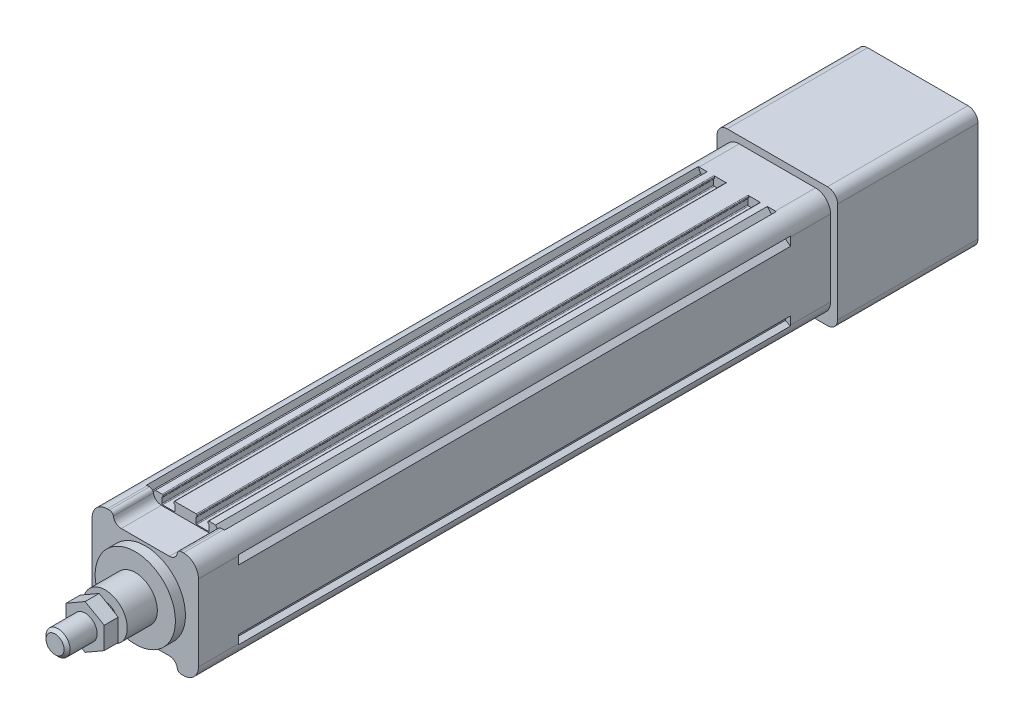
SolidWorks part; units mm, degrees
ref_plane "Front" through (0, 0, 0) normal (0, 0, 1) x (1, 0, 0)
ref_plane "Top" through (0, 0, 0) normal (0, 1, 0) x (1, 0, 0)
ref_plane "Right" through (0, 0, 0) normal (1, 0, 0) x (0, 0, -1)
sketch "草图1" plane through (0, 0, 0) normal (0, 0, 1) x (1, 0, 0)
  line L0 (19.7737, 3) -> (23.3, 3)
  line L1 (23.3, 3) -> (23.3, -3)
  line L2 (23.3, -3) -> (19.7737, -3)
  line L3 (-19.7737, -3) -> (-23.3, -3)
  line L4 (-23.3, -3) -> (-23.3, 3)
  line L5 (-23.3, 3) -> (-19.7737, 3)
  line L6 (-18.2, 24) -> (-19.4434, 26.4869)
  line L7 (-26.4869, 19.4434) -> (-24, 18.2)
  line L8 (-24, 18.2) -> (-24, 17.1)
  line L9 (-24, 17.1) -> (-26.5, 15)
  line L10 (-26.5, 15) -> (-26.5, -15)
  line L11 (-26.5, -15) -> (-24, -17.1)
  line L12 (-24, -17.1) -> (-24, -18.2)
  line L13 (-24, -18.2) -> (-26.4869, -19.4434)
  line L14 (-19.4434, -26.4869) -> (-18.2, -24)
  line L15 (-18.2, -24) -> (-17.1, -24)
  line L16 (-17.1, -24) -> (-15, -26.5)
  line L17 (-15, -26.5) -> (-11.65, -26.5)
  line L18 (-11.25, -26.1) -> (-11.25, -25.6)
  line L19 (-11.65, -25.2) -> (-11.75, -25.2)
  line L20 (-11.75, -25.2) -> (-11.75, -22.4)
  line L21 (-11.35, -22) -> (-5.65, -22)
  line L22 (-5.25, -22.4) -> (-5.25, -25.2)
  line L23 (-5.25, -25.2) -> (-5.35, -25.2)
  line L24 (-5.75, -25.6) -> (-5.75, -26.1)
  line L25 (-5.35, -26.5) -> (5.35, -26.5)
  line L26 (5.75, -26.1) -> (5.75, -25.6)
  line L27 (5.35, -25.2) -> (5.25, -25.2)
  line L28 (5.25, -25.2) -> (5.25, -22.4)
  line L29 (5.65, -22) -> (11.35, -22)
  line L30 (11.75, -22.4) -> (11.75, -25.2)
  line L31 (11.75, -25.2) -> (11.65, -25.2)
  line L32 (11.25, -25.6) -> (11.25, -26.1)
  line L33 (11.65, -26.5) -> (15, -26.5)
  line L34 (15, -26.5) -> (17.1, -24)
  line L35 (17.1, -24) -> (18.2, -24)
  line L36 (18.2, -24) -> (19.4434, -26.4869)
  line L37 (26.4869, -19.4434) -> (24, -18.2)
  line L38 (24, -18.2) -> (24, -17.1)
  line L39 (24, -17.1) -> (26.5, -15)
  line L40 (26.5, -15) -> (26.5, 15)
  line L41 (26.5, 15) -> (24, 17.1)
  line L42 (24, 17.1) -> (24, 18.2)
  line L43 (24, 18.2) -> (26.4869, 19.4434)
  line L44 (19.4434, 26.4869) -> (18.2, 24)
  line L45 (18.2, 24) -> (17.1, 24)
  line L46 (17.1, 24) -> (15, 26.5)
  line L47 (15, 26.5) -> (11.65, 26.5)
  line L48 (11.25, 26.1) -> (11.25, 25.6)
  line L49 (11.65, 25.2) -> (11.75, 25.2)
  line L50 (11.75, 25.2) -> (11.75, 22.4)
  line L51 (11.35, 22) -> (5.65, 22)
  line L52 (5.25, 22.4) -> (5.25, 25.2)
  line L53 (5.25, 25.2) -> (5.35, 25.2)
  line L54 (5.75, 25.6) -> (5.75, 26.1)
  line L55 (5.35, 26.5) -> (-5.35, 26.5)
  line L56 (-5.75, 26.1) -> (-5.75, 25.6)
  line L57 (-5.35, 25.2) -> (-5.25, 25.2)
  line L58 (-5.25, 25.2) -> (-5.25, 22.4)
  line L59 (-5.65, 22) -> (-11.35, 22)
  line L60 (-11.75, 22.4) -> (-11.75, 25.2)
  line L61 (-11.75, 25.2) -> (-11.65, 25.2)
  line L62 (-11.25, 25.6) -> (-11.25, 26.1)
  line L63 (-11.65, 26.5) -> (-15, 26.5)
  line L64 (-15, 26.5) -> (-17.1, 24)
  line L65 (-17.1, 24) -> (-18.2, 24)
  arc A0 (19.7737, 3) -> (-19.7737, 3) centre (0, 0) ccw
  arc A1 (-19.7737, -3) -> (19.7737, -3) centre (0, 0) ccw
  circle A2 centre (19, 19) radius 2.1
  circle A3 centre (19, -19) radius 2.1
  circle A4 centre (-19, -19) radius 2.1
  circle A5 centre (-19, 19) radius 2.1
  arc A6 (-19.4434, 26.4869) -> (-26.4869, 19.4434) centre (-19, 19) ccw
  arc A7 (-26.4869, -19.4434) -> (-19.4434, -26.4869) centre (-19, -19) ccw
  arc A8 (-11.65, -26.5) -> (-11.25, -26.1) centre (-11.65, -26.1) ccw
  arc A9 (-11.25, -25.6) -> (-11.65, -25.2) centre (-11.65, -25.6) ccw
  arc A10 (-11.35, -22) -> (-11.75, -22.4) centre (-11.35, -22.4) ccw
  arc A11 (-5.25, -22.4) -> (-5.65, -22) centre (-5.65, -22.4) ccw
  arc A12 (-5.35, -25.2) -> (-5.75, -25.6) centre (-5.35, -25.6) ccw
  arc A13 (-5.75, -26.1) -> (-5.35, -26.5) centre (-5.35, -26.1) ccw
  arc A14 (5.35, -26.5) -> (5.75, -26.1) centre (5.35, -26.1) ccw
  arc A15 (5.75, -25.6) -> (5.35, -25.2) centre (5.35, -25.6) ccw
  arc A16 (5.65, -22) -> (5.25, -22.4) centre (5.65, -22.4) ccw
  arc A17 (11.75, -22.4) -> (11.35, -22) centre (11.35, -22.4) ccw
  arc A18 (11.65, -25.2) -> (11.25, -25.6) centre (11.65, -25.6) ccw
  arc A19 (11.25, -26.1) -> (11.65, -26.5) centre (11.65, -26.1) ccw
  arc A20 (19.4434, -26.4869) -> (26.4869, -19.4434) centre (19, -19) ccw
  arc A21 (26.4869, 19.4434) -> (19.4434, 26.4869) centre (19, 19) ccw
  arc A22 (11.65, 26.5) -> (11.25, 26.1) centre (11.65, 26.1) ccw
  arc A23 (11.25, 25.6) -> (11.65, 25.2) centre (11.65, 25.6) ccw
  arc A24 (11.35, 22) -> (11.75, 22.4) centre (11.35, 22.4) ccw
  arc A25 (5.25, 22.4) -> (5.65, 22) centre (5.65, 22.4) ccw
  arc A26 (5.35, 25.2) -> (5.75, 25.6) centre (5.35, 25.6) ccw
  arc A27 (5.75, 26.1) -> (5.35, 26.5) centre (5.35, 26.1) ccw
  arc A28 (-5.35, 26.5) -> (-5.75, 26.1) centre (-5.35, 26.1) ccw
  arc A29 (-5.75, 25.6) -> (-5.35, 25.2) centre (-5.35, 25.6) ccw
  arc A30 (-5.65, 22) -> (-5.25, 22.4) centre (-5.65, 22.4) ccw
  arc A31 (-11.75, 22.4) -> (-11.35, 22) centre (-11.35, 22.4) ccw
  arc A32 (-11.65, 25.2) -> (-11.25, 25.6) centre (-11.65, 25.6) ccw
  arc A33 (-11.25, 26.1) -> (-11.65, 26.5) centre (-11.65, 26.1) ccw
extrude "凸台-拉伸1" add sketch "草图1" along normal blind 275
sketch "草图6" plane through (0, 0, 275) normal (0, 0, 1) x (1, 0, 0)
  line L0 (0, 0) -> (19, 0) construction
  line L2 (-26.5, -19) -> (-26.5, 19)
  line L3 (-19, 26.5) -> (-17.9161, 26.5)
  line L4 (26.5, -19) -> (26.5, 19)
  line L5 (-26.5, -26.5) -> (26.5, 26.5) construction
  line L6 (-26.5, 26.5) -> (26.5, -26.5) construction
  line L7 (-12, 21.5) -> (12, 21.5)
  line L9 (19, 26.5) -> (17.9161, 26.5)
  line L10 (19, -26.5) -> (17.9161, -26.5)
  line L11 (-12, -21.5) -> (12, -21.5)
  line L12 (-19, -26.5) -> (-17.9161, -26.5)
  arc A0 (12, 21.5) -> (15.9441, 24.8333) centre (12, 25.5) ccw
  arc A1 (-15.9441, 24.8333) -> (-12, 21.5) centre (-12, 25.5) ccw
  arc A2 (-15.9441, 24.8333) -> (-17.9161, 26.5) centre (-17.9161, 24.5) ccw
  arc A3 (15.9441, 24.8333) -> (17.9161, 26.5) centre (17.9161, 24.5) cw
  arc A4 (-26.5, -19) -> (-19, -26.5) centre (-19, -19) ccw
  arc A5 (19, -26.5) -> (26.5, -19) centre (19, -19) ccw
  arc A6 (26.5, 19) -> (19, 26.5) centre (19, 19) ccw
  arc A7 (-26.5, 19) -> (-19, 26.5) centre (-19, 19) cw
  arc A8 (15.9441, -24.8333) -> (17.9161, -26.5) centre (17.9161, -24.5) ccw
  arc A9 (12, -21.5) -> (15.9441, -24.8333) centre (12, -25.5) cw
  arc A10 (-15.9441, -24.8333) -> (-12, -21.5) centre (-12, -25.5) cw
  arc A11 (-15.9441, -24.8333) -> (-17.9161, -26.5) centre (-17.9161, -24.5) cw
  point P0 (0, 0)
  point P9 (0, 21.5)
  point P13 (20, 20.8461)
  point P16 (-12, 20.8461)
  dimension "D5" = 4
  dimension "D6" = 2
  dimension "D7" = 2
  dimension "D9" = 7.5
  dimension "D1" = 53
  dimension "D2" = 53
  dimension "D3" = 26.5
  dimension "D4" = 24
  dimension "D8" = 5
extrude "凸台-拉伸2" add sketch "草图6" along normal blind 20
sketch "草图7" plane through (0, 0, 295) normal (0, 0, 1) x (1, 0, 0)
  circle A0 centre (0, 0) radius 20
  dimension "D1" = 40
extrude "凸台-拉伸3" add sketch "草图7" along normal blind 5
sketch "草图9" plane through (0, 0, 300) normal (0, 0, 1) x (1, 0, 0)
  circle A0 centre (0, 0) radius 11
  dimension "D1" = 22
extrude "凸台-拉伸4" add sketch "草图9" along normal blind 15
sketch "草图10" plane through (0, 0, 315) normal (0, 0, 1) x (1, 0, 0)
  circle A0 centre (0, 0) radius 6
  dimension "D1" = 12
extrude "凸台-拉伸5" add sketch "草图10" along normal blind 25
sketch "草图11" plane through (0, 0, 0) normal (0, 0, -1) x (-1, 0, 0)
  line L1 (-19, -26.5) -> (19, -26.5)
  line L2 (-26.5, -19) -> (-26.5, 19)
  line L3 (-19, 26.5) -> (19, 26.5)
  line L4 (26.5, -19) -> (26.5, 19)
  line L5 (-26.5, -26.5) -> (26.5, 26.5) construction
  line L6 (-26.5, 26.5) -> (26.5, -26.5) construction
  arc A0 (-26.5, -19) -> (-19, -26.5) centre (-19, -19) ccw
  arc A1 (19, -26.5) -> (26.5, -19) centre (19, -19) ccw
  arc A2 (26.5, 19) -> (19, 26.5) centre (19, 19) ccw
  arc A3 (-26.5, 19) -> (-19, 26.5) centre (-19, 19) cw
  point P0 (0, 0)
  dimension "D3" = 7.5
  dimension "D1" = 53
  dimension "D2" = 53
extrude "凸台-拉伸6" add sketch "草图11" along normal blind 20
sketch "草图12" plane through (0, 0, -20) normal (0, 0, -1) x (-1, 0, 0)
  line L1 (-25, -30) -> (25, -30)
  line L2 (-30, -25) -> (-30, 25)
  line L3 (-25, 30) -> (25, 30)
  line L4 (30, -25) -> (30, 25)
  line L5 (-30, -30) -> (30, 30) construction
  line L6 (-30, 30) -> (30, -30) construction
  arc A0 (-30, -25) -> (-25, -30) centre (-25, -25) ccw
  arc A1 (25, -30) -> (30, -25) centre (25, -25) ccw
  arc A2 (30, 25) -> (25, 30) centre (25, 25) ccw
  arc A3 (-30, 25) -> (-25, 30) centre (-25, 25) cw
  point P0 (0, 0)
  dimension "D3" = 5
  dimension "D1" = 60
  dimension "D2" = 60
extrude "凸台-拉伸7" add sketch "草图12" along normal blind 70
sketch "草图14" plane through (0, 0, -90) normal (0, 0, -1) x (-1, 0, 0)
  circle A0 centre (0, 0) radius 19
  dimension "D1" = 38
extrude "切除-拉伸2" cut sketch "草图14" against normal blind 70
hole_wizard "M6 螺纹孔1" positions "草图15" profile "草图16" tap size "M6" standard "GB"
sketch "草图15" plane through (-26.5, 0, 0) normal (-1, 0, 0) x (0, 0, 1)
  line L0 (-20, -25) -> (-20, 25) construction
  line L1 (295, 19) -> (295, -19) construction
  point P0 (285, 11)
  point P2 (285, -11)
  point P4 (-10, 11)
  point P6 (-10, -11)
  dimension "D1" = 10
  dimension "D2" = 10
  dimension "D3" = 11
  dimension "D4" = 11
  dimension "D5" = 10
  dimension "D6" = 10
  dimension "D7" = 22
  dimension "D8" = 11
sketch "草图16" plane through (-26.5, 11, 285) normal (0, 1, 0) x (0, 0, 1)
  line L0 (0, 0) -> (0, 16.5022)
  line L1 (0, 16.5022) -> (2.5, 15)
  line L2 (2.5, 15) -> (2.5, 0)
  line L5 (2.5, 0) -> (0, 0)
  line L10 (0, 16.5022) -> (-2.5, 15) construction
  line L11 (0, -6.35) -> (0, 107.95) construction
  dimension "螺纹孔钻头直径" = 5
  dimension "螺纹孔钻头深度" = 15
  dimension "导头角度" = 118
cosmetic thread "孔螺蚊线4" parameters "D1"=12, "D2"=6
cosmetic thread "孔螺蚊线5" parameters "D1"=12, "D2"=6
cosmetic thread "孔螺蚊线6" parameters "D1"=12, "D2"=6
cosmetic thread "孔螺蚊线7" parameters "D1"=12, "D2"=6
chamfer "倒角1" distance 1.5 angle 45 1 edges at (6, 0, 340)
sketch "草图17" plane through (0, 0, 315) normal (0, 0, 1) x (1, 0, 0)
  line L1 (0, 10.9697) -> (-9.5, 5.4848)
  line L2 (-9.5, 5.4848) -> (-9.5, -5.4848)
  line L3 (-9.5, -5.4848) -> (0, -10.9697)
  line L4 (0, -10.9697) -> (9.5, -5.4848)
  line L5 (9.5, -5.4848) -> (9.5, 5.4848)
  line L6 (9.5, 5.4848) -> (0, 10.9697)
  circle A0 centre (0, 0) radius 9.5 construction
  dimension "D1" = 19
extrude "凸台-拉伸8" add sketch "草图17" along normal blind 7 from offset 3
